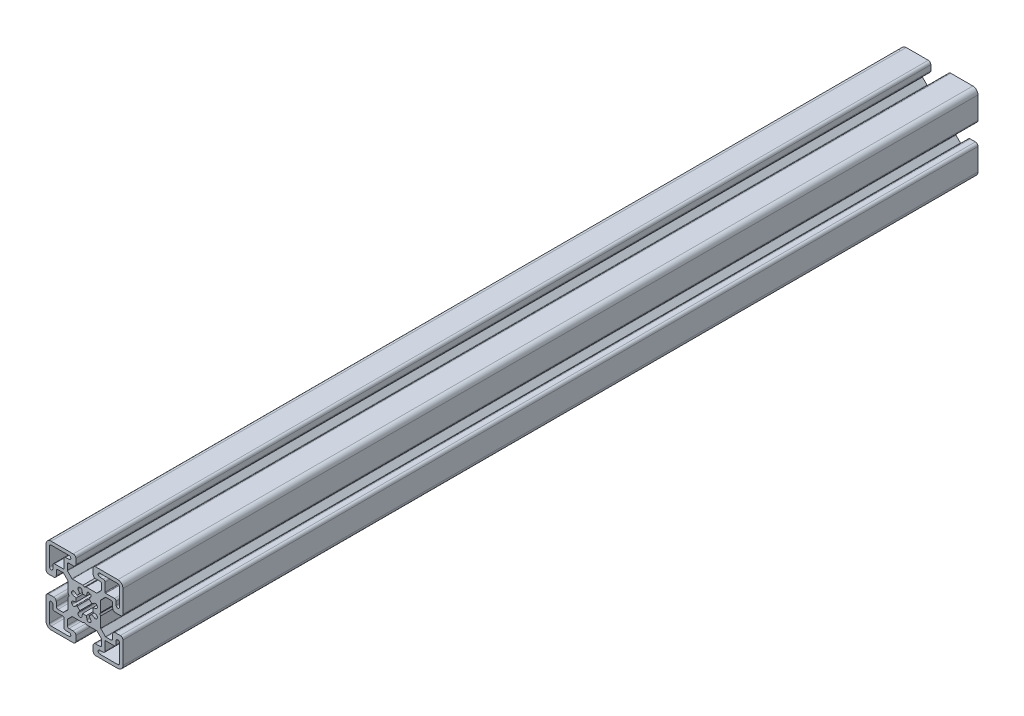
SolidWorks part; units mm, degrees
material "6061 Alloy"
ref_plane "Front Plane" through (0, 0, 0) normal (0, 0, 1) x (1, 0, 0)
ref_plane "Top Plane" through (0, 0, 0) normal (0, 1, 0) x (1, 0, 0)
ref_plane "Right Plane" through (0, 0, 0) normal (1, 0, 0) x (0, 0, -1)
sketch "Sketch1" plane through (0, 0, 0) normal (0, 0, 1) x (1, 0, 0)
  line L0 (-8.0293, -14.4831) -> (-6.0293, -14.4831)
  line L1 (-6.0293, -16.4831) -> (-16.5293, -16.4831)
  line L2 (-17.5293, -15.4831) -> (-17.5293, -4.9831)
  line L3 (-15.5293, -4.9831) -> (-15.5293, -6.9831)
  line L4 (-14.5293, -7.9831) -> (-9.4093, -7.9831)
  line L5 (-9.0293, -8.3631) -> (-9.0293, -13.4831)
  line L6 (-15.5293, 15.0169) -> (-15.5293, 13.0169)
  line L7 (-17.5293, 13.0169) -> (-17.5293, 23.5169)
  line L8 (-16.5293, 24.5169) -> (-6.0293, 24.5169)
  line L9 (-6.0293, 22.5169) -> (-8.0293, 22.5169)
  line L10 (-9.0293, 21.5169) -> (-9.0293, 16.3969)
  line L11 (-9.4093, 16.0169) -> (-14.5293, 16.0169)
  line L12 (14.9707, 16.3969) -> (14.9707, 21.5169)
  line L13 (13.9707, 22.5169) -> (11.9707, 22.5169)
  line L14 (11.9707, 24.5169) -> (22.4707, 24.5169)
  line L15 (23.4707, 23.5169) -> (23.4707, 13.0169)
  line L16 (21.4707, 13.0169) -> (21.4707, 15.0169)
  line L17 (20.4707, 16.0169) -> (15.3507, 16.0169)
  line L18 (8.8137, 0.2931) -> (7.1867, 1.3289)
  line L19 (5.6584, -0.1993) -> (6.6943, -1.826)
  line L20 (4.4692, -2.7478) -> (4.0512, -0.865)
  line L21 (1.8899, -0.8649) -> (1.4721, -2.7476)
  line L22 (-0.7531, -1.8261) -> (0.2827, -0.1991)
  line L23 (-1.2455, 1.3292) -> (-2.8722, 0.2933)
  line L24 (-3.794, 2.5184) -> (-1.9112, 2.9364)
  line L25 (-1.9111, 5.0977) -> (-3.7938, 5.5155)
  line L26 (-2.8723, 7.7407) -> (-1.2453, 6.7049)
  line L27 (0.283, 8.2331) -> (-0.7529, 9.8598)
  line L28 (1.4722, 10.7816) -> (1.8902, 8.8987)
  line L29 (4.0515, 8.8987) -> (4.4693, 10.7814)
  line L30 (6.6945, 9.8599) -> (5.6587, 8.2329)
  line L31 (7.1869, 6.7046) -> (8.8136, 7.7405)
  line L32 (9.7354, 5.5154) -> (7.8526, 5.0973)
  line L33 (7.8525, 2.936) -> (9.7352, 2.5183)
  line L34 (21.4707, -6.9831) -> (21.4707, -4.9831)
  line L35 (23.4707, -4.9831) -> (23.4707, -15.4831)
  line L36 (22.4707, -16.4831) -> (11.9707, -16.4831)
  line L37 (11.9707, -14.4831) -> (13.9707, -14.4831)
  line L38 (14.9707, -13.4831) -> (14.9707, -8.3631)
  line L39 (15.3507, -7.9831) -> (20.4707, -7.9831)
  line L40 (2.0707, -5.4831) -> (2.9707, -4.968)
  line L41 (2.9707, -4.968) -> (3.8707, -5.4831)
  line L42 (3.8707, -5.4831) -> (10.0223, -5.4831)
  line L43 (10.291, -5.5944) -> (12.9094, -8.2128)
  line L44 (13.0207, -8.4815) -> (13.0207, -11.4831)
  line L45 (12.0207, -12.4831) -> (9.5557, -12.4831)
  line L46 (8.0357, -14.0031) -> (8.0357, -16.9631)
  line L47 (9.5557, -18.4831) -> (22.4707, -18.4831)
  line L48 (25.4707, -15.4831) -> (25.4707, -2.5681)
  line L49 (23.9507, -1.0481) -> (20.9907, -1.0481)
  line L50 (19.4707, -2.5681) -> (19.4707, -5.0331)
  line L51 (18.4707, -6.0331) -> (15.4691, -6.0331)
  line L52 (15.2004, -5.9218) -> (12.582, -3.3034)
  line L53 (12.4707, -3.0347) -> (12.4707, 3.1169)
  line L54 (12.4707, 3.1169) -> (11.9511, 4.0169)
  line L55 (11.9511, 4.0169) -> (12.4707, 4.9169)
  line L56 (12.4707, 4.9169) -> (12.4707, 11.0685)
  line L57 (12.582, 11.3372) -> (15.2004, 13.9556)
  line L58 (15.4691, 14.0669) -> (18.4707, 14.0669)
  line L59 (19.4707, 13.0669) -> (19.4707, 10.6019)
  line L60 (20.9907, 9.0819) -> (23.9507, 9.0819)
  line L61 (25.4707, 10.6019) -> (25.4707, 23.5169)
  line L62 (22.4707, 26.5169) -> (9.5557, 26.5169)
  line L63 (8.0357, 24.9969) -> (8.0357, 22.0369)
  line L64 (9.5557, 20.5169) -> (12.0207, 20.5169)
  line L65 (13.0207, 19.5169) -> (13.0207, 16.5153)
  line L66 (12.9094, 16.2466) -> (10.291, 13.6282)
  line L67 (10.0223, 13.5169) -> (3.8707, 13.5169)
  line L68 (3.8707, 13.5169) -> (2.9707, 13.0017)
  line L69 (2.9707, 13.0017) -> (2.0707, 13.5169)
  line L70 (2.0707, 13.5169) -> (-4.0809, 13.5169)
  line L71 (-4.3496, 13.6282) -> (-6.968, 16.2466)
  line L72 (-7.0793, 16.5153) -> (-7.0793, 19.5169)
  line L73 (-6.0793, 20.5169) -> (-3.6143, 20.5169)
  line L74 (-2.0943, 22.0369) -> (-2.0943, 24.9969)
  line L75 (-3.6143, 26.5169) -> (-16.5293, 26.5169)
  line L76 (-19.5293, 23.5169) -> (-19.5293, 10.6019)
  line L77 (-18.0093, 9.0819) -> (-15.0493, 9.0819)
  line L78 (-13.5293, 10.6019) -> (-13.5293, 13.0669)
  line L79 (-12.5293, 14.0669) -> (-9.5277, 14.0669)
  line L80 (-9.259, 13.9556) -> (-6.6406, 11.3372)
  line L81 (-6.5293, 11.0685) -> (-6.5293, 4.9169)
  line L82 (-6.5293, 4.9169) -> (-6.0097, 4.0169)
  line L83 (-6.0097, 4.0169) -> (-6.5293, 3.1169)
  line L84 (-6.5293, 3.1169) -> (-6.5293, -3.0347)
  line L85 (-6.6406, -3.3034) -> (-9.259, -5.9218)
  line L86 (-9.5277, -6.0331) -> (-12.5293, -6.0331)
  line L87 (-13.5293, -5.0331) -> (-13.5293, -2.5681)
  line L88 (-15.0493, -1.0481) -> (-18.0093, -1.0481)
  line L89 (-19.5293, -2.5681) -> (-19.5293, -15.4831)
  line L90 (-16.5293, -18.4831) -> (-3.6143, -18.4831)
  line L91 (-2.0943, -16.9631) -> (-2.0943, -14.0031)
  line L92 (-3.6143, -12.4831) -> (-6.0793, -12.4831)
  line L93 (-7.0793, -11.4831) -> (-7.0793, -8.4815)
  line L94 (-6.968, -8.2128) -> (-4.3496, -5.5944)
  line L95 (-4.0809, -5.4831) -> (2.0707, -5.4831)
  arc A0 (-9.0293, -13.4831) -> (-8.0293, -14.4831) centre (-8.0293, -13.4831) ccw
  arc A1 (-6.0293, -16.4831) -> (-6.0293, -14.4831) centre (-6.0293, -15.4831) ccw
  arc A2 (-17.5293, -15.4831) -> (-16.5293, -16.4831) centre (-16.5293, -15.4831) ccw
  arc A3 (-15.5293, -4.9831) -> (-17.5293, -4.9831) centre (-16.5293, -4.9831) ccw
  arc A4 (-15.5293, -6.9831) -> (-14.5293, -7.9831) centre (-14.5293, -6.9831) ccw
  arc A5 (-9.0293, -8.3631) -> (-9.4093, -7.9831) centre (-9.4093, -8.3631) ccw
  arc A6 (-14.5293, 16.0169) -> (-15.5293, 15.0169) centre (-14.5293, 15.0169) ccw
  arc A7 (-17.5293, 13.0169) -> (-15.5293, 13.0169) centre (-16.5293, 13.0169) ccw
  arc A8 (-16.5293, 24.5169) -> (-17.5293, 23.5169) centre (-16.5293, 23.5169) ccw
  arc A9 (-6.0293, 22.5169) -> (-6.0293, 24.5169) centre (-6.0293, 23.5169) ccw
  arc A10 (-8.0293, 22.5169) -> (-9.0293, 21.5169) centre (-8.0293, 21.5169) ccw
  arc A11 (-9.4093, 16.0169) -> (-9.0293, 16.3969) centre (-9.4093, 16.3969) ccw
  arc A12 (14.9707, 16.3969) -> (15.3507, 16.0169) centre (15.3507, 16.3969) ccw
  arc A13 (14.9707, 21.5169) -> (13.9707, 22.5169) centre (13.9707, 21.5169) ccw
  arc A14 (11.9707, 24.5169) -> (11.9707, 22.5169) centre (11.9707, 23.5169) ccw
  arc A15 (23.4707, 23.5169) -> (22.4707, 24.5169) centre (22.4707, 23.5169) ccw
  arc A16 (21.4707, 13.0169) -> (23.4707, 13.0169) centre (22.4707, 13.0169) ccw
  arc A17 (21.4707, 15.0169) -> (20.4707, 16.0169) centre (20.4707, 15.0169) ccw
  arc A18 (10.2621, 0.7252) -> (10.454, 1.1885) centre (2.9707, 4.0169) ccw
  arc A19 (8.8137, 0.2931) -> (10.2621, 0.7252) centre (9.3507, 1.1367) ccw
  arc A20 (5.6584, -0.1993) -> (7.1867, 1.3289) centre (2.9707, 4.0169) ccw
  arc A21 (6.2622, -3.2746) -> (6.6943, -1.826) centre (5.8508, -2.3632) ccw
  arc A22 (5.799, -3.4665) -> (6.2622, -3.2746) centre (2.9707, 4.0169) ccw
  arc A23 (4.4692, -2.7478) -> (5.799, -3.4665) centre (5.4454, -2.5311) ccw
  arc A24 (1.8899, -0.8649) -> (4.0512, -0.865) centre (2.9707, 4.0169) ccw
  arc A25 (0.1423, -3.4664) -> (1.4721, -2.7476) centre (0.4958, -2.531) ccw
  arc A26 (-0.321, -3.2745) -> (0.1423, -3.4664) centre (2.9707, 4.0169) ccw
  arc A27 (-0.7531, -1.8261) -> (-0.321, -3.2745) centre (0.0905, -2.3631) ccw
  arc A28 (-1.2455, 1.3292) -> (0.2827, -0.1991) centre (2.9707, 4.0169) ccw
  arc A29 (-4.3208, 0.7254) -> (-2.8722, 0.2933) centre (-3.4094, 1.1368) ccw
  arc A30 (-4.5127, 1.1886) -> (-4.3208, 0.7254) centre (2.9707, 4.0169) ccw
  arc A31 (-3.794, 2.5184) -> (-4.5127, 1.1886) centre (-3.5773, 1.5422) ccw
  arc A32 (-1.9111, 5.0977) -> (-1.9112, 2.9364) centre (2.9707, 4.0169) ccw
  arc A33 (-4.5126, 6.8453) -> (-3.7938, 5.5155) centre (-3.5772, 6.4917) ccw
  arc A34 (-4.3207, 7.3085) -> (-4.5126, 6.8453) centre (2.9707, 4.0169) ccw
  arc A35 (-2.8723, 7.7407) -> (-4.3207, 7.3085) centre (-3.4093, 6.8971) ccw
  arc A36 (0.283, 8.2331) -> (-1.2453, 6.7049) centre (2.9707, 4.0169) ccw
  arc A37 (-0.3208, 11.3084) -> (-0.7529, 9.8598) centre (0.0906, 10.3969) ccw
  arc A38 (0.1424, 11.5003) -> (-0.3208, 11.3084) centre (2.9707, 4.0169) ccw
  arc A39 (1.4722, 10.7816) -> (0.1424, 11.5003) centre (0.496, 10.5648) ccw
  arc A40 (4.0515, 8.8987) -> (1.8902, 8.8987) centre (2.9707, 4.0169) ccw
  arc A41 (5.7991, 11.5002) -> (4.4693, 10.7814) centre (5.4456, 10.5648) ccw
  arc A42 (6.2624, 11.3083) -> (5.7991, 11.5002) centre (2.9707, 4.0169) ccw
  arc A43 (6.6945, 9.8599) -> (6.2624, 11.3083) centre (5.8509, 10.3969) ccw
  arc A44 (7.1869, 6.7046) -> (5.6587, 8.2329) centre (2.9707, 4.0169) ccw
  arc A45 (10.2622, 7.3084) -> (8.8136, 7.7405) centre (9.3508, 6.897) ccw
  arc A46 (10.4541, 6.8451) -> (10.2622, 7.3084) centre (2.9707, 4.0169) ccw
  arc A47 (9.7354, 5.5154) -> (10.4541, 6.8451) centre (9.5187, 6.4916) ccw
  arc A48 (7.8525, 2.936) -> (7.8526, 5.0973) centre (2.9707, 4.0169) ccw
  arc A49 (10.454, 1.1885) -> (9.7352, 2.5183) centre (9.5186, 1.542) ccw
  arc A50 (20.4707, -7.9831) -> (21.4707, -6.9831) centre (20.4707, -6.9831) ccw
  arc A51 (23.4707, -4.9831) -> (21.4707, -4.9831) centre (22.4707, -4.9831) ccw
  arc A52 (22.4707, -16.4831) -> (23.4707, -15.4831) centre (22.4707, -15.4831) ccw
  arc A53 (11.9707, -14.4831) -> (11.9707, -16.4831) centre (11.9707, -15.4831) ccw
  arc A54 (13.9707, -14.4831) -> (14.9707, -13.4831) centre (13.9707, -13.4831) ccw
  arc A55 (15.3507, -7.9831) -> (14.9707, -8.3631) centre (15.3507, -8.3631) ccw
  arc A56 (10.291, -5.5944) -> (10.0223, -5.4831) centre (10.0223, -5.8631) ccw
  arc A57 (13.0207, -8.4815) -> (12.9094, -8.2128) centre (12.6407, -8.4815) ccw
  arc A58 (12.0207, -12.4831) -> (13.0207, -11.4831) centre (12.0207, -11.4831) ccw
  arc A59 (9.5557, -12.4831) -> (8.0357, -14.0031) centre (9.5557, -14.0031) ccw
  arc A60 (8.0357, -16.9631) -> (9.5557, -18.4831) centre (9.5557, -16.9631) ccw
  arc A61 (22.4707, -18.4831) -> (25.4707, -15.4831) centre (22.4707, -15.4831) ccw
  arc A62 (25.4707, -2.5681) -> (23.9507, -1.0481) centre (23.9507, -2.5681) ccw
  arc A63 (20.9907, -1.0481) -> (19.4707, -2.5681) centre (20.9907, -2.5681) ccw
  arc A64 (18.4707, -6.0331) -> (19.4707, -5.0331) centre (18.4707, -5.0331) ccw
  arc A65 (15.2004, -5.9218) -> (15.4691, -6.0331) centre (15.4691, -5.6531) ccw
  arc A66 (12.4707, -3.0347) -> (12.582, -3.3034) centre (12.8507, -3.0347) ccw
  arc A67 (12.582, 11.3372) -> (12.4707, 11.0685) centre (12.8507, 11.0685) ccw
  arc A68 (15.4691, 14.0669) -> (15.2004, 13.9556) centre (15.4691, 13.6869) ccw
  arc A69 (19.4707, 13.0669) -> (18.4707, 14.0669) centre (18.4707, 13.0669) ccw
  arc A70 (19.4707, 10.6019) -> (20.9907, 9.0819) centre (20.9907, 10.6019) ccw
  arc A71 (23.9507, 9.0819) -> (25.4707, 10.6019) centre (23.9507, 10.6019) ccw
  arc A72 (25.4707, 23.5169) -> (22.4707, 26.5169) centre (22.4707, 23.5169) ccw
  arc A73 (9.5557, 26.5169) -> (8.0357, 24.9969) centre (9.5557, 24.9969) ccw
  arc A74 (8.0357, 22.0369) -> (9.5557, 20.5169) centre (9.5557, 22.0369) ccw
  arc A75 (13.0207, 19.5169) -> (12.0207, 20.5169) centre (12.0207, 19.5169) ccw
  arc A76 (12.9094, 16.2466) -> (13.0207, 16.5153) centre (12.6407, 16.5153) ccw
  arc A77 (10.0223, 13.5169) -> (10.291, 13.6282) centre (10.0223, 13.8969) ccw
  arc A78 (-4.3496, 13.6282) -> (-4.0809, 13.5169) centre (-4.0809, 13.8969) ccw
  arc A79 (-7.0793, 16.5153) -> (-6.968, 16.2466) centre (-6.6993, 16.5153) ccw
  arc A80 (-6.0793, 20.5169) -> (-7.0793, 19.5169) centre (-6.0793, 19.5169) ccw
  arc A81 (-3.6143, 20.5169) -> (-2.0943, 22.0369) centre (-3.6143, 22.0369) ccw
  arc A82 (-2.0943, 24.9969) -> (-3.6143, 26.5169) centre (-3.6143, 24.9969) ccw
  arc A83 (-16.5293, 26.5169) -> (-19.5293, 23.5169) centre (-16.5293, 23.5169) ccw
  arc A84 (-19.5293, 10.6019) -> (-18.0093, 9.0819) centre (-18.0093, 10.6019) ccw
  arc A85 (-15.0493, 9.0819) -> (-13.5293, 10.6019) centre (-15.0493, 10.6019) ccw
  arc A86 (-12.5293, 14.0669) -> (-13.5293, 13.0669) centre (-12.5293, 13.0669) ccw
  arc A87 (-9.259, 13.9556) -> (-9.5277, 14.0669) centre (-9.5277, 13.6869) ccw
  arc A88 (-6.5293, 11.0685) -> (-6.6406, 11.3372) centre (-6.9093, 11.0685) ccw
  arc A89 (-6.6406, -3.3034) -> (-6.5293, -3.0347) centre (-6.9093, -3.0347) ccw
  arc A90 (-9.5277, -6.0331) -> (-9.259, -5.9218) centre (-9.5277, -5.6531) ccw
  arc A91 (-13.5293, -5.0331) -> (-12.5293, -6.0331) centre (-12.5293, -5.0331) ccw
  arc A92 (-13.5293, -2.5681) -> (-15.0493, -1.0481) centre (-15.0493, -2.5681) ccw
  arc A93 (-18.0093, -1.0481) -> (-19.5293, -2.5681) centre (-18.0093, -2.5681) ccw
  arc A94 (-19.5293, -15.4831) -> (-16.5293, -18.4831) centre (-16.5293, -15.4831) ccw
  arc A95 (-3.6143, -18.4831) -> (-2.0943, -16.9631) centre (-3.6143, -16.9631) ccw
  arc A96 (-2.0943, -14.0031) -> (-3.6143, -12.4831) centre (-3.6143, -14.0031) ccw
  arc A97 (-7.0793, -11.4831) -> (-6.0793, -12.4831) centre (-6.0793, -11.4831) ccw
  arc A98 (-6.968, -8.2128) -> (-7.0793, -8.4815) centre (-6.6993, -8.4815) ccw
  arc A99 (-4.0809, -5.4831) -> (-4.3496, -5.5944) centre (-4.0809, -5.8631) ccw
extrude "Extrude1" add sketch "Sketch1" along normal blind 500
